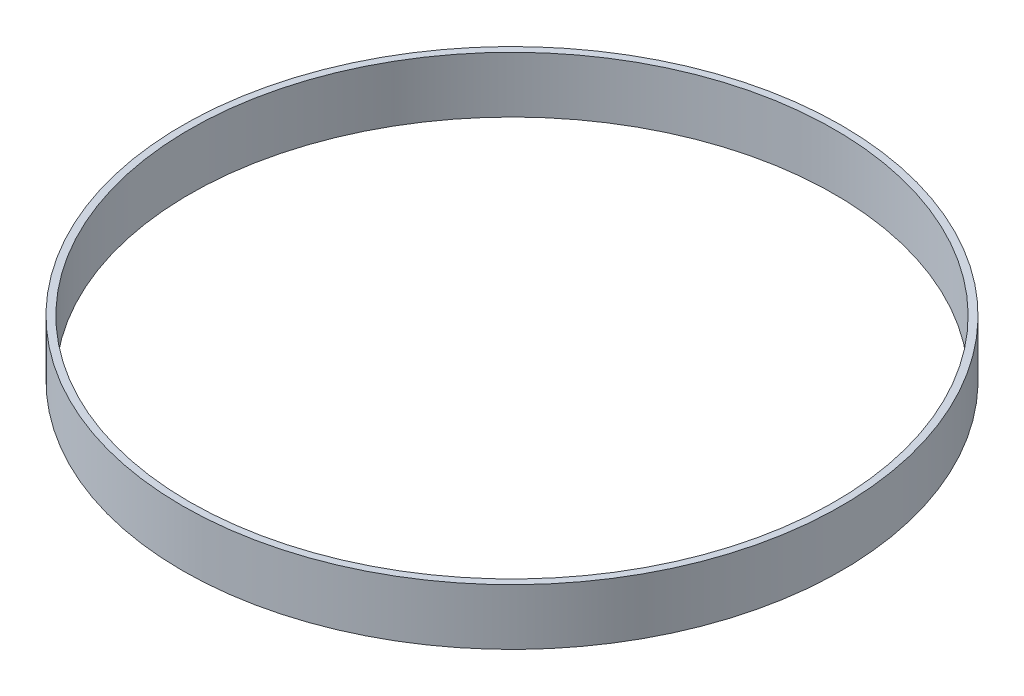
SolidWorks part; units mm, degrees
ref_plane "Plan de face" through (0, 0, 0) normal (0, 0, 1) x (1, 0, 0)
ref_plane "Plan de dessus" through (0, 0, 0) normal (0, 1, 0) x (1, 0, 0)
ref_plane "Plan de droite" through (0, 0, 0) normal (1, 0, 0) x (0, 0, -1)
sketch "Esquisse1" plane through (0, 0, 0) normal (0, 1, 0) x (1, 0, 0)
  circle A0 centre (0, 0) radius 47
  circle A1 centre (0, 0) radius 46
  dimension "D1" = 94
  dimension "D2" = 1
extrude "Boss.-Extru.1" add sketch "Esquisse1" along normal blind 8
